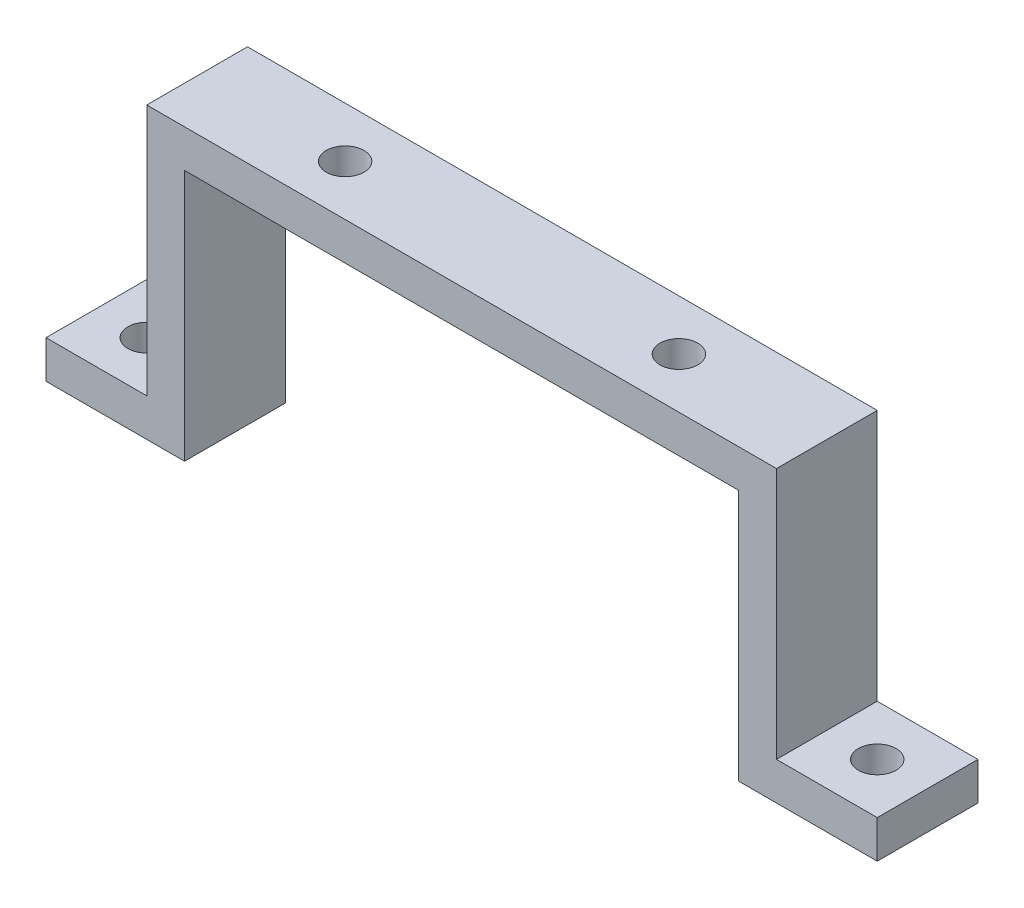
SolidWorks part; units mm, degrees
ref_plane "Front Plane" through (0, 0, 0) normal (0, 0, 1) x (1, 0, 0)
ref_plane "Top Plane" through (0, 0, 0) normal (0, 1, 0) x (1, 0, 0)
ref_plane "Right Plane" through (0, 0, 0) normal (1, 0, 0) x (0, 0, -1)
sketch "Sketch1" plane through (0, 0, 0) normal (0, 1, 0) x (1, 0, 0)
  line L0 (-55, 0) -> (55, 0) construction
  line L1 (-25, -4) -> (25, -4)
  line L2 (-25, -4) -> (-25, 4)
  line L3 (-25, 4) -> (25, 4)
  line L4 (25, -4) -> (25, 4)
  line L5 (-25, -4) -> (25, 4) construction
  line L6 (-25, 4) -> (25, -4) construction
  line L7 (0, -55) -> (0, 55) construction
  circle A0 centre (-13.25, 0) radius 1.5
  circle A1 centre (13.25, 0) radius 1.5
  point P0 (0, 0)
  dimension "D3" = 3
  dimension "D5" = 3
  dimension "D1" = 8
  dimension "D2" = 50
  dimension "D4" = 13.25
  dimension "D6" = 13.25
extrude "Boss-Extrude1" add sketch "Sketch1" along normal blind 3
sketch "Sketch2" plane through (0, 0, 0) normal (0, -1, 0) x (1, 0, 0)
  line L0 (-25, 4) -> (25, 4) construction
  line L1 (-25, -4) -> (-22, -4)
  line L2 (-25, -4) -> (-25, 4)
  line L3 (-25, 4) -> (-22, 4)
  line L4 (-22, -4) -> (-22, 4)
  dimension "D1" = 3
extrude "Boss-Extrude2" add sketch "Sketch2" along normal blind 20
ref_plane "Plane1" through (0, -20, 0) normal (0, -1, 0) x (-1, 0, 0)
sketch "Sketch3" plane through (0, -20, 0) normal (0, -1, 0) x (-1, 0, 0)
  line L0 (25, 4) -> (22, 4) construction
  line L1 (25, 4) -> (33, 4)
  line L2 (25, 4) -> (25, -4)
  line L3 (25, -4) -> (33, -4)
  line L4 (33, 4) -> (33, -4)
  line L5 (22, -4) -> (-25, -4) construction
  line L6 (-7.15, 0) -> (7.15, 0) construction
  circle A0 centre (29, 0) radius 1.5
  point P12 (0, 0)
  point P13 (29, 4)
  dimension "D2" = 3
  dimension "D1" = 8
extrude "Boss-Extrude3" add sketch "Sketch3" against normal blind 3
mirror "Mirror1" about plane through (0, 0, 0) normal (1, 0, 0) of "Boss-Extrude2", "Boss-Extrude3"
